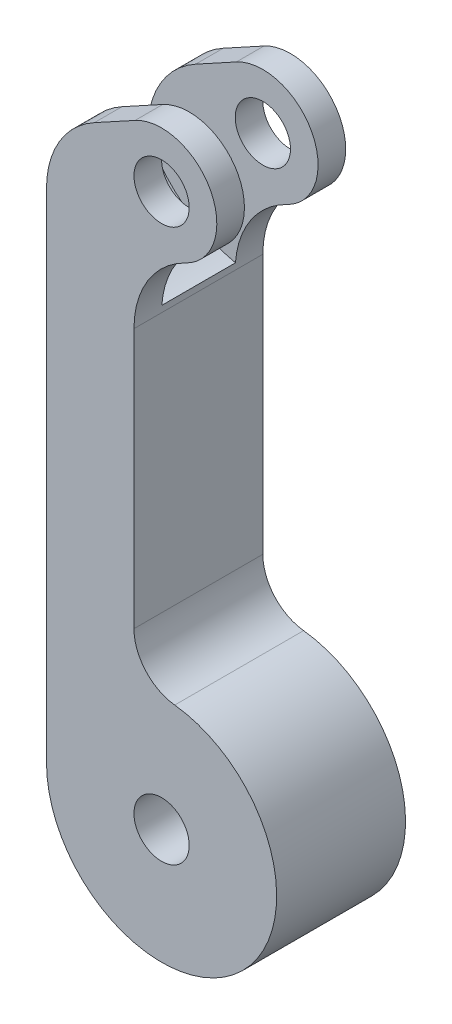
SolidWorks part; units mm, degrees
ref_plane "Alzado" through (0, 0, 0) normal (0, 0, 1) x (1, 0, 0)
ref_plane "Planta" through (0, 0, 0) normal (0, 1, 0) x (1, 0, 0)
ref_plane "Vista lateral" through (0, 0, 0) normal (1, 0, 0) x (0, 0, -1)
sketch "Croquis1" plane through (0, 0, 0) normal (0, 0, 1) x (1, 0, 0)
  line L0 (0, 0) -> (0, 60) construction
  line L1 (-12.5, 60) -> (-12.5, 0)
  line L2 (-3, 0) -> (-3, 60)
  line L3 (-12.5, 60) -> (-2.88, 65.2636)
  circle A0 centre (0, 0) radius 12.5
  circle A1 centre (0, 0) radius 3
  circle A2 centre (0, 60) radius 12.5
  circle A3 centre (0, 60) radius 3
  circle A4 centre (0, 60) radius 6
  dimension "D1" = 6
  dimension "D2" = 25
  dimension "D3" = 6
  dimension "D4" = 25
  dimension "D7" = 12
  dimension "D5" = 60
  dimension "D6" = 9.5
extrude "Saliente-Extruir1" add sketch "Croquis1" along normal blind 14 contours A4 L3 A2 L2 | A2 L1 A0 L2 | L0 A1 L2 A0 | L0 A4 L2 A3 | A4 L0 A3 L2 | A1 L0 A0 L2
fillet "Redondeo1" radius 10 1 edges at (-12.5, 60, 7)
fillet "Redondeo2" radius 10 1 edges at (-3, 54.8038, 7)
fillet "Redondeo3" radius 5 1 edges at (-3, 12.1347, 7)
sketch "Croquis2" plane through (0, 0, 14) normal (0, 0, 1) x (1, 0, 0)
  circle A0 centre (0, 60) radius 14
  dimension "D1" = 28
extrude "Cortar-Extruir1" cut sketch "Croquis2" against normal blind 8 from offset 3
